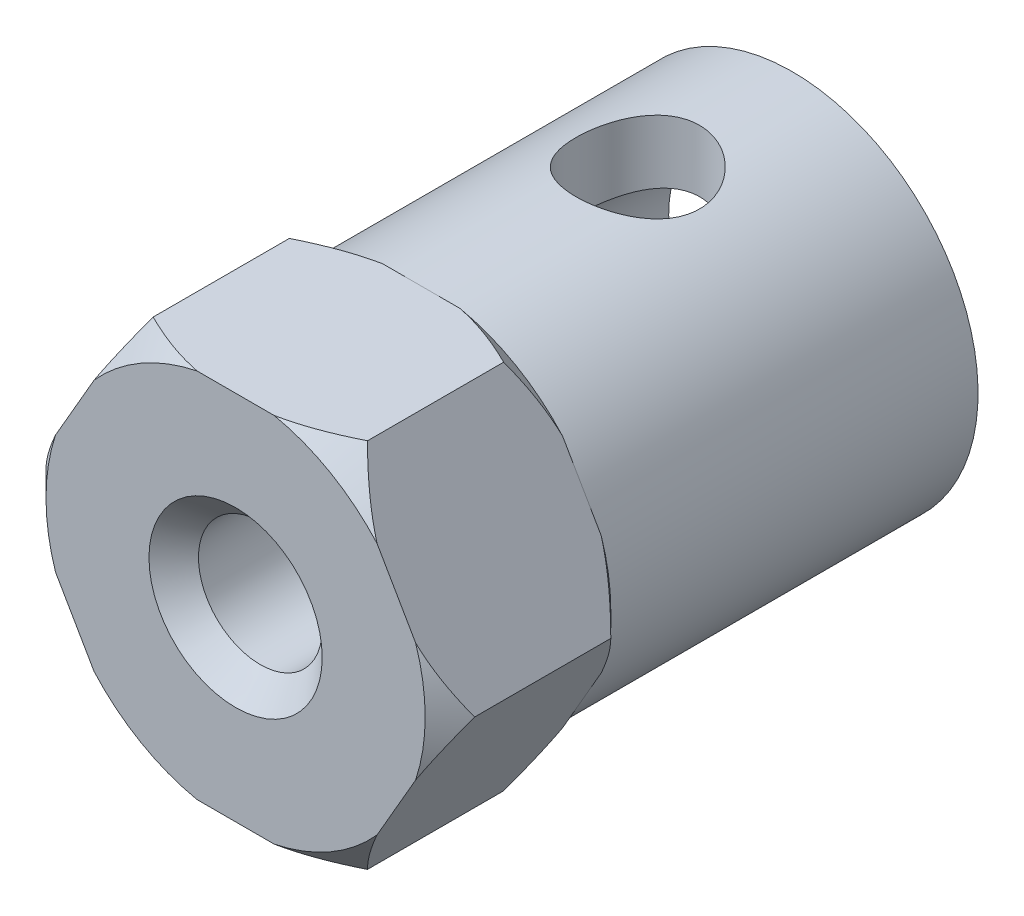
SolidWorks part; units mm, degrees
ref_plane "前视基准面" through (0, 0, 0) normal (0, 0, 1) x (1, 0, 0)
ref_plane "上视基准面" through (0, 0, 0) normal (0, 1, 0) x (1, 0, 0)
ref_plane "右视基准面" through (0, 0, 0) normal (1, 0, 0) x (0, 0, -1)
sketch "草图1" plane through (0, 0, 0) normal (0, 0, 1) x (1, 0, 0)
  line L1 (6.9282, 0) -> (3.4641, 6)
  line L2 (3.4641, 6) -> (-3.4641, 6)
  line L3 (-3.4641, 6) -> (-6.9282, 0)
  line L4 (-6.9282, 0) -> (-3.4641, -6)
  line L5 (-3.4641, -6) -> (3.4641, -6)
  line L6 (3.4641, -6) -> (6.9282, 0)
  circle A0 centre (0, 0) radius 6 construction
extrude "凸台-拉伸1" add sketch "草图1" along normal blind 6
sketch "草图2" plane through (0, 0, 0) normal (0, 0, -1) x (-1, 0, 0)
  circle A0 centre (0, 0) radius 6
  circle A1 centre (0, 0) radius 4
  dimension "D1" = 12
  dimension "D2" = 8
extrude "凸台-拉伸2" add sketch "草图2" along normal blind 12 contours A0 A1
sketch "草图3" plane through (0, 0, 6) normal (0, 0, 1) x (1, 0, 0)
  circle A0 centre (0, 0) radius 2
  dimension "D1" = 4
extrude "切除-拉伸1" cut sketch "草图3" against normal blind 12
chamfer "倒角1" distance 0.8 angle 45 1 edges at (2, 0, 6)
sketch "草图4" plane through (0, 0, 0) normal (0, 1, 0) x (1, 0, 0)
  line L0 (0, 12) -> (0, 7)
  line L1 (4, 12) -> (-4, 12) construction
  circle A0 centre (0, 7) radius 2
  dimension "D2" = 4
  dimension "D1" = 5
extrude "切除-拉伸2" cut sketch "草图4" against normal mid plane 12
sketch "草图5" plane through (0, 0, 0) normal (0, 1, 0) x (1, 0, 0)
  line L0 (-6.9282, 0) -> (-6.1282, 0)
  line L1 (-6.9282, 0) -> (-5.1962, 0) construction
  line L2 (-6.1282, 0) -> (-6.9282, -0.8)
  line L3 (-6.9282, -0.8) -> (-6.9282, 0)
  line L4 (-6.9282, 0) -> (-6.9282, -6) construction
  line L6 (-6.9282, -6) -> (-3.4641, -6) construction
  line L9 (-6.9282, -6) -> (-6.9282, -3) construction
  line L10 (-6.9282, -3) -> (-3.4641, -3) construction
  line L11 (-6.9282, -5.2) -> (-6.9282, -6)
  line L12 (-6.1282, -6) -> (-6.9282, -5.2)
  line L13 (-6.9282, -6) -> (-6.1282, -6)
  line L14 (0, 0) -> (0, -2.0212) construction
  dimension "D1" = 0.8
  dimension "D2" = 0.8
revolve "切除-旋转1" cut sketch "草图5" angle 360 about L14
